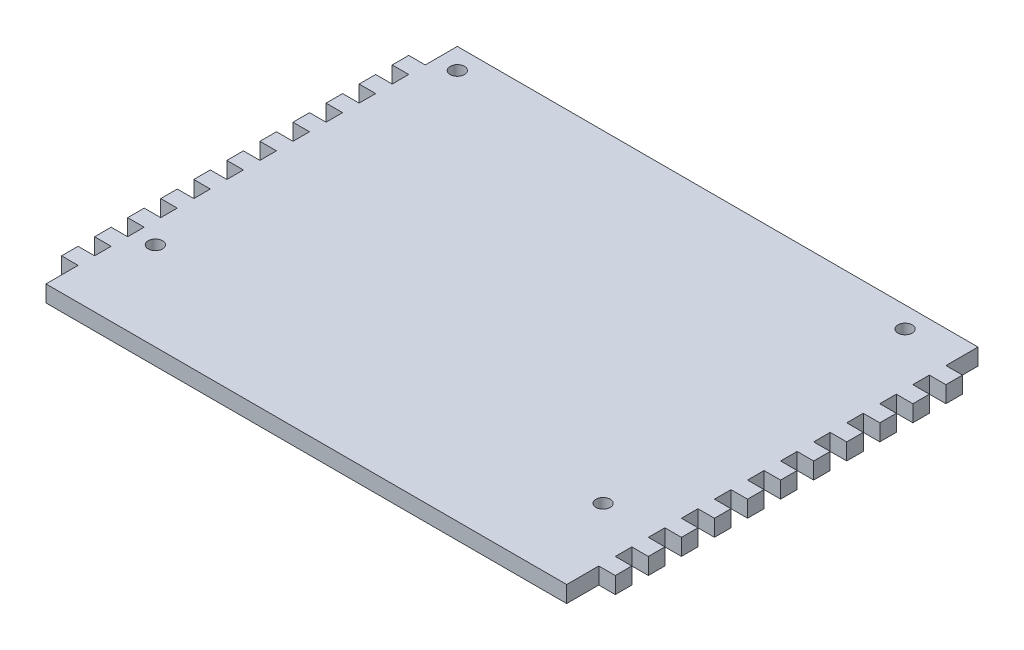
SolidWorks part; units mm, degrees
ref_plane "Front Plane" through (0, 0, 0) normal (0, 0, 1) x (1, 0, 0)
ref_plane "Top Plane" through (0, 0, 0) normal (0, 1, 0) x (1, 0, 0)
ref_plane "Right Plane" through (0, 0, 0) normal (1, 0, 0) x (0, 0, -1)
sketch "Sketch1" plane through (0, 0, 0) normal (0, 1, 0) x (1, 0, 0)
  line L1 (50, -39.5) -> (-50, -39.5)
  line L2 (50, -39.5) -> (50, 39.5)
  line L3 (50, 39.5) -> (-50, 39.5)
  line L4 (-50, -39.5) -> (-50, 39.5)
  line L5 (50, -39.5) -> (-50, 39.5) construction
  line L6 (50, 39.5) -> (-50, -39.5) construction
  point P0 (0, 0)
  dimension "D1" = 100
  dimension "D2" = 79
extrude "Boss-Extrude1" add sketch "Sketch1" along normal blind 3.175
sketch "Sketch2" plane through (0, 3.175, 0) normal (0, 1, 0) x (1, 0, 0)
  line L1 (50, -39.5) -> (-50, -39.5) construction
  line L2 (50, -39.5) -> (50, 39.5) construction
  line L3 (50, 39.5) -> (-50, 39.5) construction
  line L4 (-50, -39.5) -> (-50, 39.5) construction
  line L5 (50, -39.5) -> (-50, 39.5) construction
  line L6 (50, 39.5) -> (-50, -39.5) construction
  point P0 (0, 0)
  dimension "D1" = 79
  dimension "D2" = 100
  dimension "D3" = 0
sketch "Sketch3" plane through (0, 3.175, 0) normal (0, 1, 0) x (1, 0, 0)
  line L0 (50, 39.5) -> (-50, 39.5) construction
  line L1 (-50, -39.5) -> (-50, 39.5) construction
  line L2 (50, -39.5) -> (50, 39.5) construction
  line L3 (50, -39.5) -> (-50, -39.5) construction
  circle A0 centre (-46, 35.5) radius 1.375
  circle A1 centre (-46, -22.5) radius 1.375
  circle A2 centre (40, 35.5) radius 1.375
  circle A3 centre (40, -22.5) radius 1.375
  dimension "D1" = 2.75
  dimension "D2" = 4
  dimension "D3" = 4
  dimension "D4" = 4
  dimension "D5" = 10
  dimension "D6" = 10
  dimension "D7" = 17
  dimension "D8" = 17
  dimension "D9" = 4
extrude "Cut-Extrude1" cut sketch "Sketch3" against normal blind 10
sketch "Sketch4" plane through (0, 3.175, 0) normal (0, 1, 0) x (1, 0, 0)
  line L1 (-50, 39.5) -> (-56.35, 39.5)
  line L2 (-50, 39.5) -> (-50, -39.5)
  line L3 (-50, -39.5) -> (-56.35, -39.5)
  line L4 (-56.35, 39.5) -> (-56.35, -39.5)
  line L5 (50, -39.5) -> (56.35, -39.5)
  line L6 (50, -39.5) -> (50, 39.5)
  line L7 (50, 39.5) -> (56.35, 39.5)
  line L8 (56.35, -39.5) -> (56.35, 39.5)
  dimension "D1" = 6.35
  dimension "D2" = 6.35
extrude "Boss-Extrude2" add sketch "Sketch4" against normal up to surface (3.175 mm away) up to face at (-46, 0, 23.875)
sketch "Sketch5" plane through (0, 3.175, 0) normal (0, 1, 0) x (1, 0, 0)
  line L0 (-50, -39.5) -> (-50, 39.5) construction
  line L1 (-53.175, 4.7625) -> (-50, 4.7625)
  line L2 (-53.175, 4.7625) -> (-53.175, 1.5875)
  line L3 (-53.175, 1.5875) -> (-50, 1.5875)
  line L4 (-50, 4.7625) -> (-50, 1.5875)
  dimension "D1" = 3.175
  dimension "D2" = 3.175
  dimension "D3" = 1.5875
  dimension "D4" = 0
extrude "Cut-Extrude2" cut sketch "Sketch5" against normal blind 10
pattern_linear "LPattern1" count 7 spacing 6.35 along (0, 0, 1) count 7 spacing 6.35 along (0, 0, -1) skipping (0, 6) of "Cut-Extrude2"
sketch "Sketch6" plane through (0, 3.175, 0) normal (0, 1, 0) x (1, 0, 0)
  line L1 (-53.175, 36.5125) -> (-50, 36.5125)
  line L2 (-53.175, 36.5125) -> (-53.175, 39.5)
  line L3 (-53.175, 39.5) -> (-50, 39.5)
  line L4 (-50, 36.5125) -> (-50, 39.5)
  line L5 (-53.175, -36.5125) -> (-50, -36.5125)
  line L6 (-53.175, -36.5125) -> (-53.175, -39.5)
  line L7 (-53.175, -39.5) -> (-50, -39.5)
  line L8 (-50, -36.5125) -> (-50, -39.5)
extrude "Cut-Extrude3" cut sketch "Sketch6" against normal blind 10
mirror "Mirror1" about plane through (0, 0, 0) normal (1, 0, 0) of "LPattern1", "Cut-Extrude3", "Cut-Extrude2"
sketch "Sketch7" plane through (0, 3.175, 0) normal (0, 1, 0) x (1, 0, 0)
  line L1 (56.35, 39.5) -> (62.35, 39.5)
  line L2 (56.35, 39.5) -> (56.35, -39.5)
  line L3 (56.35, -39.5) -> (62.35, -39.5)
  line L4 (62.35, 39.5) -> (62.35, -39.5)
  line L5 (-56.35, 39.5) -> (-62.35, 39.5)
  line L6 (-56.35, 39.5) -> (-56.35, -39.5)
  line L7 (-56.35, -39.5) -> (-62.35, -39.5)
  line L8 (-62.35, 39.5) -> (-62.35, -39.5)
  circle A0 centre (-59.35, 31.5) radius 1.5
  circle A1 centre (-59.35, -31.5) radius 1.5
  circle A2 centre (59.35, 31.5) radius 1.5
  circle A3 centre (59.35, -31.5) radius 1.5
  dimension "D3" = 3
  dimension "D4" = 3
  dimension "D5" = 3
  dimension "D6" = 3
  dimension "D1" = 6
  dimension "D2" = 6
  dimension "D7" = 8
  dimension "D8" = 8
  dimension "D9" = 8
  dimension "D10" = 8
extrude "Boss-Extrude3" add sketch "Sketch7" against normal up to surface (3.175 mm away) up to face at (51.5875, 0, 28.575)
sketch "Sketch8" plane through (0, 3.175, 0) normal (0, 1, 0) x (1, 0, 0)
  line L1 (-62.35, 39.5) -> (-65.525, 39.5)
  line L2 (-62.35, 39.5) -> (-62.35, -39.5)
  line L3 (-62.35, -39.5) -> (-65.525, -39.5)
  line L4 (-65.525, 39.5) -> (-65.525, -39.5)
  line L5 (62.35, 39.5) -> (65.525, 39.5)
  line L6 (62.35, 39.5) -> (62.35, -39.5)
  line L7 (62.35, -39.5) -> (65.525, -39.5)
  line L8 (65.525, 39.5) -> (65.525, -39.5)
  dimension "D1" = 3.175
  dimension "D2" = 3.175
extrude "Boss-Extrude4" add sketch "Sketch8" against normal up to surface (3.175 mm away) up to face at (51.5875, 0, 28.575)
sketch "Sketch9" plane through (0, 3.175, 0) normal (0, 1, 0) x (1, 0, 0)
  line L1 (59.35, -31.5) -> (-59.35, -31.5) construction
  line L2 (59.35, -31.5) -> (59.35, 31.5) construction
  line L3 (59.35, 31.5) -> (-59.35, 31.5) construction
  line L4 (-59.35, -31.5) -> (-59.35, 31.5) construction
  line L5 (59.35, -31.5) -> (-59.35, 31.5) construction
  line L6 (59.35, 31.5) -> (-59.35, -31.5) construction
  point P0 (0, 0)
  dimension "D1" = 118.7
  dimension "D2" = 63
sketch "Sketch10" plane through (0, 3.175, 0) normal (0, 1, 0) x (1, 0, 0)
  line L1 (-65.525, 39.5) -> (-53.175, 39.5)
  line L2 (-65.525, 39.5) -> (-65.525, -39.5)
  line L3 (-65.525, -39.5) -> (-53.175, -39.5)
  line L4 (-53.175, 39.5) -> (-53.175, -39.5)
  line L5 (65.525, 39.5) -> (53.175, 39.5)
  line L6 (65.525, 39.5) -> (65.525, -39.5)
  line L7 (65.525, -39.5) -> (53.175, -39.5)
  line L8 (53.175, 39.5) -> (53.175, -39.5)
extrude "Cut-Extrude4" cut sketch "Sketch10" against normal blind 10
